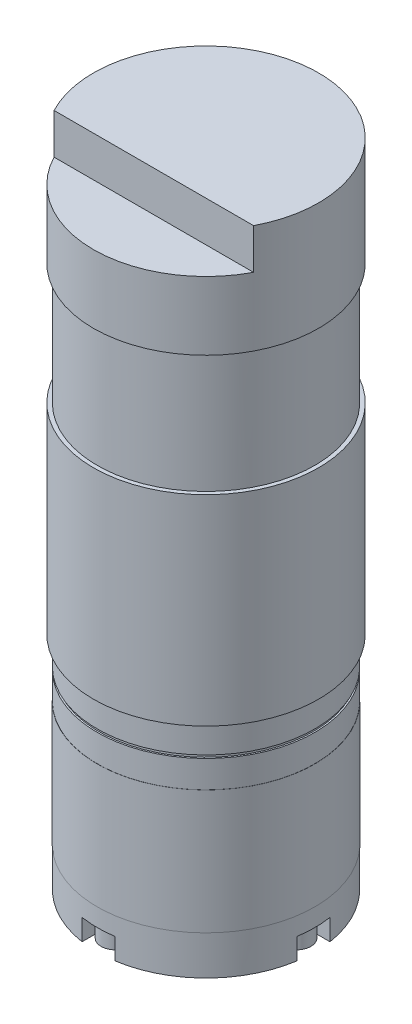
SolidWorks part; units mm, degrees
ref_plane "Front Plane" through (0, 0, 0) normal (0, 0, 1) x (1, 0, 0)
ref_plane "Top Plane" through (0, 0, 0) normal (0, 1, 0) x (1, 0, 0)
ref_plane "Right Plane" through (0, 0, 0) normal (1, 0, 0) x (0, 0, -1)
sketch "Sketch1" plane through (0, 0, 0) normal (0, 1, 0) x (1, 0, 0)
  circle A0 centre (0, 0) radius 18
  dimension "D1" = 36
extrude "Boss-Extrude1" add sketch "Sketch1" along normal blind 89.8
sketch "Sketch2" plane through (0, 89.8, 0) normal (0, 1, 0) x (1, 0, 0)
  circle A0 centre (0, 0) radius 18.65
  dimension "D1" = 37.3
extrude "Boss-Extrude2" add sketch "Sketch2" along normal blind 18
ref_plane "Plane1" through (0, 69.8, 0) normal (0, -1, 0) x (-1, 0, 0)
sketch "Sketch9" plane through (0, 0, 0) normal (0, -1, 0) x (1, 0, 0)
  line L1 (4.5826, -10) -> (-4.5826, -10)
  line L2 (4.5826, 10) -> (-4.5826, 10)
  arc A0 (4.5826, -10) -> (4.5826, 10) centre (0, 0) ccw
  arc A1 (-4.5826, 10) -> (-4.5826, -10) centre (0, 0) ccw
  point P6 (0, 0)
  point P9 (0, -10)
  point P12 (0, 10)
  dimension "D1" = 22
  dimension "D2" = 9.1652
  dimension "D3" = 9.1652
extrude "Boss-Extrude4" add sketch "Sketch9" along normal blind 1.3
sketch "Sketch3" plane through (0, 69.8, 0) normal (0, -1, 0) x (-1, 0, 0)
  circle A0 centre (0, 0) radius 18.65
  dimension "D1" = 37.3
extrude "Boss-Extrude3" add sketch "Sketch3" along normal blind 33.2
sketch "Sketch11" plane through (0, -1.3, 0) normal (0, -1, 0) x (1, 0, 0)
  circle A0 centre (0, 0) radius 4
  dimension "D1" = 8
extrude "Cut-Extrude1" cut sketch "Sketch11" against normal blind 10.3
sketch "Sketch13" plane through (0, 107.8, 0) normal (0, 1, 0) x (1, 0, 0)
  line L1 (-16.5227, -8.65) -> (16.5227, -8.65)
  circle A0 centre (0, 0) radius 18.65 construction
  arc A1 (16.5227, -8.65) -> (-16.5227, -8.65) centre (0, 0) cw
  point P9 (0, -8.65)
extrude "Cut-Extrude2" cut sketch "Sketch13" against normal blind 6.7
sketch "Sketch14" plane through (0, 0, 0) normal (0, -1, 0) x (1, 0, 0)
  circle A5 centre (-9.8995, 9.8995) radius 1.5
  circle A6 centre (9.8995, 9.8995) radius 1.5
  circle A7 centre (9.8995, -9.8995) radius 1.5
  circle A8 centre (-9.8995, -9.8995) radius 1.5
  point P8 (0, 0)
  point P15 (0, 0)
  point P17 (0, 0)
  point P20 (0, 0)
  dimension "D2" = 3
  dimension "D3" = 3
  dimension "D4" = 3
  dimension "D5" = 3
extrude "Cut-Extrude3" cut sketch "Sketch14" against normal blind 10
ref_plane "Plane2" through (0, 6.5, 0) normal (0, -1, 0) x (-1, 0, 0)
sketch "Sketch16" plane through (0, 6.5, 0) normal (0, -1, 0) x (-1, 0, 0)
  circle A0 centre (0, 0) radius 18.025
  dimension "D1" = 36.05
extrude "Boss-Extrude5" add sketch "Sketch16" against normal blind 20.5
ref_plane "Plane3" through (0, 31.5, 0) normal (0, -1, 0) x (-1, 0, 0)
sketch "Sketch17" plane through (0, 31.5, 0) normal (0, -1, 0) x (-1, 0, 0)
  circle A0 centre (0, 0) radius 17.75
  circle A1 centre (0, 0) radius 19.6457
extrude "Cut-Extrude5" cut sketch "Sketch17" against normal blind 0.5
sketch "Sketch18" plane through (0, 0, 0) normal (0, -1, 0) x (1, 0, 0)
  line L0 (2.75, -15) -> (2.75, -20)
  line L1 (2.75, -20) -> (-2.75, -20)
  line L2 (-2.75, -20) -> (-2.75, -15)
  line L3 (2.75, 15) -> (2.75, 20)
  line L4 (2.75, 20) -> (-2.75, 20)
  line L5 (-2.75, 20) -> (-2.75, 15)
  line L6 (-15, 2.75) -> (-20, 2.75)
  line L7 (-20, 2.75) -> (-20, -2.75)
  line L8 (-20, -2.75) -> (-15, -2.75)
  line L9 (15, -2.75) -> (20, -2.75)
  line L10 (20, -2.75) -> (20, 2.75)
  line L11 (20, 2.75) -> (15, 2.75)
  circle A0 centre (0, 0) radius 15 construction
  arc A1 (2.75, -15) -> (-2.75, -15) centre (0, -15) ccw
  arc A5 (15, 2.75) -> (15, -2.75) centre (15, 0) ccw
  arc A6 (-2.75, 15) -> (2.75, 15) centre (0, 15) ccw
  arc A7 (-15, -2.75) -> (-15, 2.75) centre (-15, 0) ccw
  point P14 (0, 0)
  dimension "D1" = 30
  dimension "D2" = 5.5
  dimension "D3" = 5.5
  dimension "D4" = 5.5
  dimension "D5" = 5.5
  dimension "D6" = 20
  dimension "D7" = 20
  dimension "D8" = 2.75
  dimension "D9" = 20
  dimension "D10" = 20
  dimension "D11" = 2.75
extrude "Cut-Extrude6" cut sketch "Sketch18" against normal blind 3.5
sketch "Sketch19" plane through (0, 3.5, 0) normal (0, -1, 0) x (1, 0, 0)
  circle A0 centre (-15, 0) radius 2.375
  circle A1 centre (0, 15) radius 2.375
  circle A2 centre (15, 0) radius 2.375
  circle A3 centre (0, -15) radius 2.375
  point P12 (0, 0)
  dimension "D2" = 4.75
  dimension "D1" = 4
extrude "Boss-Extrude6" add sketch "Sketch19" along normal blind 3
sketch "Sketch20" plane through (0, 0.5, 0) normal (0, -1, 0) x (1, 0, 0)
  line L0 (16.5158, 0.8752) -> (15, 1.7503)
  line L1 (-1.7503, 15) -> (-0.8752, 13.4842)
  line L2 (-0.8752, 13.4842) -> (0.8752, 13.4842)
  line L3 (0.8752, 13.4842) -> (1.7503, 15)
  line L4 (1.7503, 15) -> (0.8752, 16.5158)
  line L5 (0.8752, 16.5158) -> (-0.8752, 16.5158)
  line L6 (-0.8752, 16.5158) -> (-1.7503, 15)
  line L7 (16.5158, -0.8752) -> (16.5158, 0.8752)
  line L8 (15, -1.7503) -> (16.5158, -0.8752)
  line L9 (13.4842, -0.8752) -> (15, -1.7503)
  line L10 (13.4842, 0.8752) -> (13.4842, -0.8752)
  line L11 (15, 1.7503) -> (13.4842, 0.8752)
  line L12 (0.8752, -16.5158) -> (1.7503, -15)
  line L13 (-0.8752, -16.5158) -> (0.8752, -16.5158)
  line L14 (-1.7503, -15) -> (-0.8752, -16.5158)
  line L15 (-0.8752, -13.4842) -> (-1.7503, -15)
  line L16 (0.8752, -13.4842) -> (-0.8752, -13.4842)
  line L17 (1.7503, -15) -> (0.8752, -13.4842)
  line L18 (-16.5158, -0.8752) -> (-15, -1.7503)
  line L19 (-16.5158, 0.8752) -> (-16.5158, -0.8752)
  line L20 (-15, 1.7503) -> (-16.5158, 0.8752)
  line L21 (-13.4842, 0.8752) -> (-15, 1.7503)
  line L22 (-13.4842, -0.8752) -> (-13.4842, 0.8752)
  line L23 (-15, -1.7503) -> (-13.4842, -0.8752)
  circle A0 centre (0, 15) radius 1.5158 construction
  point P30 (0, 0)
  dimension "D1" = 4
extrude "Cut-Extrude7" cut sketch "Sketch20" against normal blind 3
